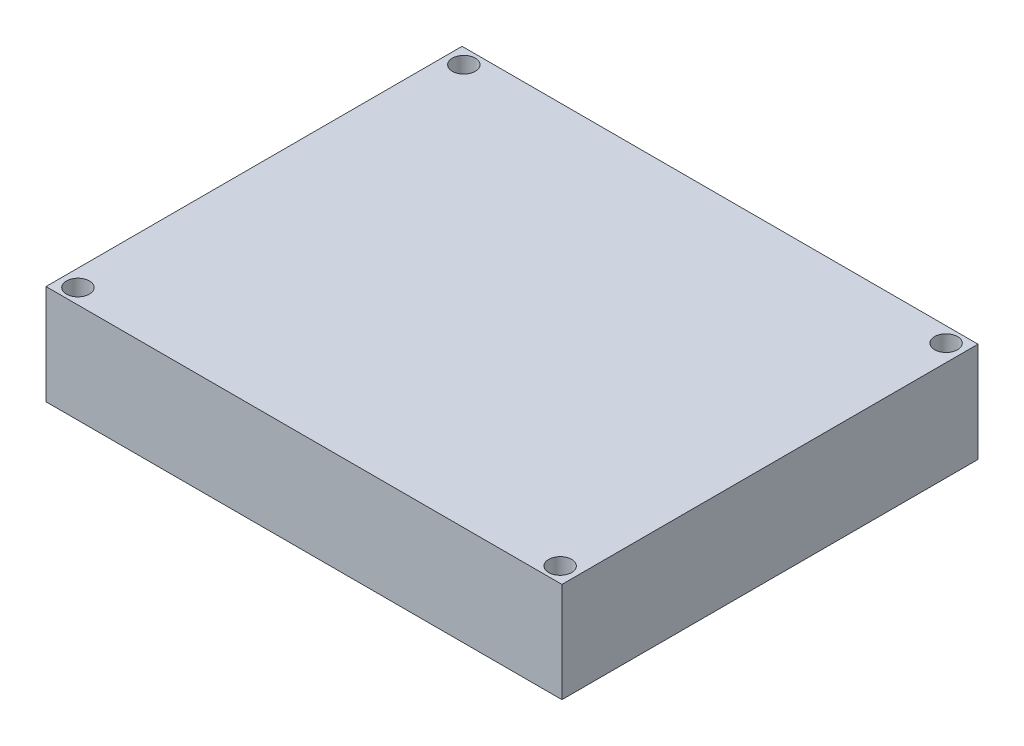
SolidWorks part; units mm, degrees
ref_plane "Alzado" through (0, 0, 0) normal (0, 0, 1) x (1, 0, 0)
ref_plane "Planta" through (0, 0, 0) normal (0, 1, 0) x (1, 0, 0)
ref_plane "Vista lateral" through (0, 0, 0) normal (1, 0, 0) x (0, 0, -1)
sketch "Croquis1" plane through (0, 345.0814, 0) normal (0, -1, 0) x (-1, 0, 0)
  line L1 (13.9911, 23.5501) -> (92.7311, 23.5501)
  line L2 (13.9911, 23.5501) -> (13.9911, 87.0501)
  line L3 (13.9911, 87.0501) -> (92.7311, 87.0501)
  line L4 (92.7311, 23.5501) -> (92.7311, 87.0501)
  line L5 (90.1611, 84.7501) -> (90.1611, 25.8501) construction
  line L6 (16.5611, 84.7501) -> (90.1611, 84.7501) construction
  circle A0 centre (90.1611, 84.7501) radius 1.75
  circle A1 centre (16.5611, 25.8501) radius 1.75
  circle A2 centre (90.1611, 25.8501) radius 1.75
  circle A3 centre (16.5611, 84.7501) radius 1.75
  point P12 (53.3611, 84.7501)
  point P13 (53.3611, 87.0501)
  point P14 (90.1611, 55.3001)
  point P15 (92.7311, 55.3001)
  dimension "D4" = 3.5
  dimension "D1" = 78.74
  dimension "D2" = 63.5
  dimension "D3" = 58.9
  dimension "D5" = 73.6
extrude "Saliente-Extruir1" add sketch "Croquis1" along normal blind 15.24
